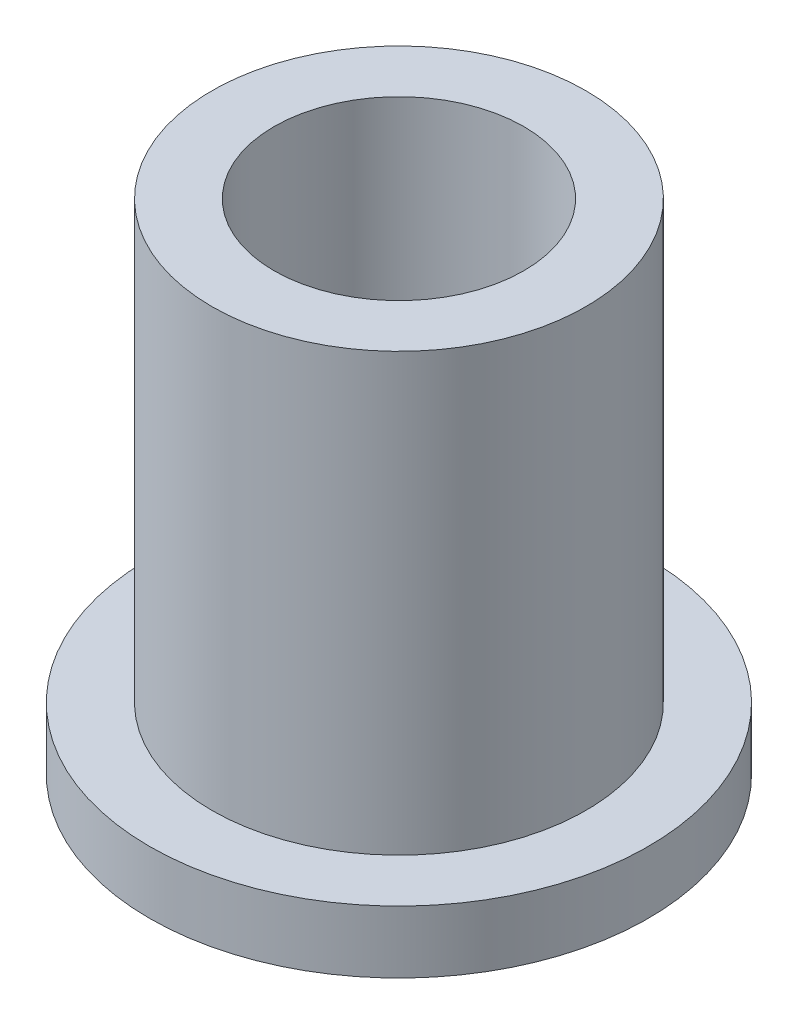
SolidWorks part; units mm, degrees
material "Commercial Bronze, UNS C22000 (90-10 Bronze)"
ref_plane "Front" through (0, 0, 0) normal (0, 0, 1) x (1, 0, 0)
ref_plane "Top" through (0, 0, 0) normal (0, 1, 0) x (1, 0, 0)
ref_plane "Right" through (0, 0, 0) normal (1, 0, 0) x (0, 0, -1)
sketch "Sketch1" plane through (0, 0, 0) normal (0, 1, 0) x (1, 0, 0)
  circle A0 centre (0, 0) radius 6.3627
  circle A1 centre (0, 0) radius 9.525
  circle A2 centre (0, 0) radius 12.7
  dimension "ID" = 12.7254
  dimension "OD" = 19.05
  dimension "FlangeOD" = 25.4
sketch "Sketch2" plane through (0, 0, 0) normal (0, 1, 0) x (1, 0, 0)
  circle A0 centre (0, 0) radius 6.3627 construction
  circle A1 centre (0, 0) radius 9.525 construction
  circle A2 centre (0, 0) radius 6.3627
  circle A3 centre (0, 0) radius 9.525
extrude "Boss-Extrude1" add sketch "Sketch2" along normal blind 25.4
sketch "Sketch3" plane through (0, 0, 0) normal (0, 1, 0) x (1, 0, 0)
  circle A0 centre (0, 0) radius 12.7 construction
  circle A1 centre (0, 0) radius 9.525 construction
  circle A2 centre (0, 0) radius 12.7
  circle A3 centre (0, 0) radius 9.525
extrude "Boss-Extrude2" add sketch "Sketch3" along normal blind 3.175
